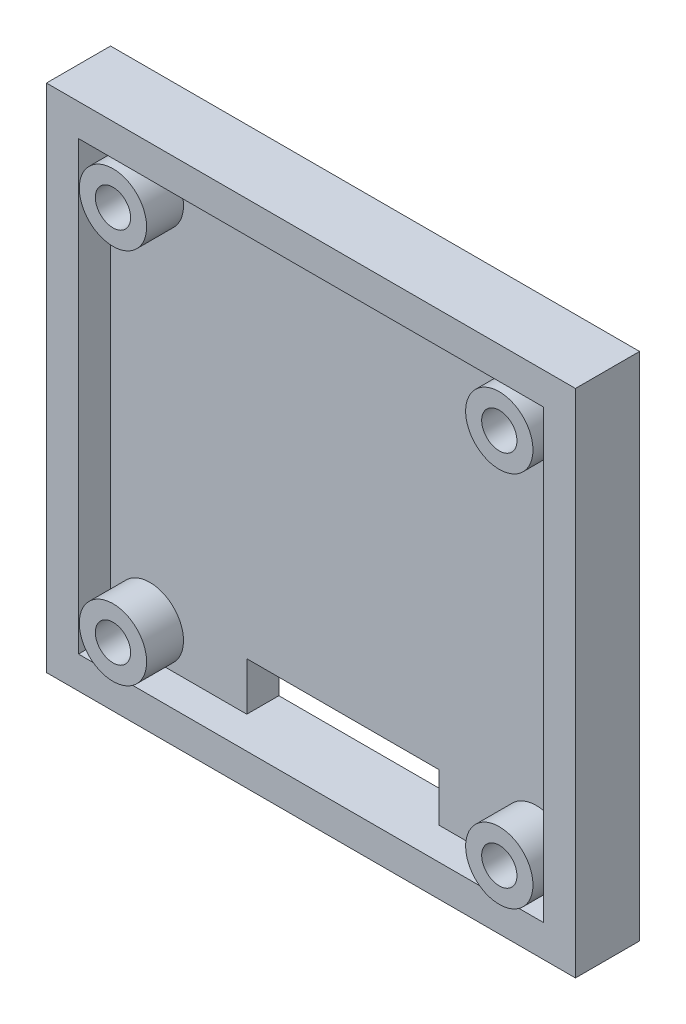
SolidWorks part; units mm, degrees
ref_plane "Front Plane" through (0, 0, 0) normal (0, 0, 1) x (1, 0, 0)
ref_plane "Top Plane" through (0, 0, 0) normal (0, 1, 0) x (1, 0, 0)
ref_plane "Right Plane" through (0, 0, 0) normal (1, 0, 0) x (0, 0, -1)
sketch "Sketch1" plane through (0, 0, 0) normal (0, 0, 1) x (1, 0, 0)
  line L1 (16.5, -15.925) -> (-16.5, -15.925)
  line L2 (16.5, -15.925) -> (16.5, 15.925)
  line L3 (16.5, 15.925) -> (-16.5, 15.925)
  line L4 (-16.5, -15.925) -> (-16.5, 15.925)
  line L5 (16.5, -15.925) -> (-16.5, 15.925) construction
  line L6 (16.5, 15.925) -> (-16.5, -15.925) construction
  line L7 (-12.05, -11.925) -> (12.05, -11.925)
  line L8 (-12.05, -11.925) -> (-12.05, 11.575)
  line L9 (-12.05, 11.575) -> (12.05, 11.575)
  line L10 (12.05, -11.925) -> (12.05, 11.575)
  line L11 (-12.05, -11.925) -> (12.05, 11.575) construction
  line L12 (-12.05, 11.575) -> (12.05, -11.925) construction
  line L17 (-6, -10.925) -> (6, -10.925)
  line L18 (-6, -10.925) -> (-6, -13.925)
  line L19 (-6, -13.925) -> (6, -13.925)
  line L20 (6, -10.925) -> (6, -13.925)
  circle A0 centre (-12.05, 11.575) radius 1.1
  circle A1 centre (12.05, 11.575) radius 1.1
  circle A2 centre (-12.05, -11.925) radius 1.1
  circle A3 centre (12.05, -11.925) radius 1.1
  point P0 (0, 0)
  point P6 (0, -0.175)
  dimension "D7" = 2.2
  dimension "D1" = 24.1
  dimension "D2" = 23.5
  dimension "D3" = 4
  dimension "D4" = 4.45
  dimension "D5" = 31.85
  dimension "D6" = 33
  dimension "D8" = 12
  dimension "D9" = 3
  dimension "D10" = 2
  dimension "D11" = 10.5
extrude "Boss-Extrude1" add sketch "Sketch1" along normal blind 2 contours L4 L1 L2 L3 A3 L7 A2 L8 A0 L9 A1 L10 | A3 L10 A1 L9 A0 L8 A2 L7 L18 L19 L20
sketch "Sketch2" plane through (0, 0, 2) normal (0, 0, 1) x (1, 0, 0)
  circle A0 centre (-12.05, 11.575) radius 2.1
  circle A1 centre (-12.05, -11.925) radius 2.1
  circle A2 centre (12.05, -11.925) radius 2.1
  circle A3 centre (12.05, 11.575) radius 2.1
  circle A4 centre (12.05, 11.575) radius 1.1
  circle A5 centre (-12.05, 11.575) radius 1.1
  circle A6 centre (-12.05, -11.925) radius 1.1
  circle A7 centre (12.05, -11.925) radius 1.1
  dimension "D1" = 1
extrude "Boss-Extrude2" add sketch "Sketch2" along normal blind 2.3
sketch "Sketch3" plane through (0, 0, 2) normal (0, 0, 1) x (1, 0, 0)
  line L1 (-16.5, 15.925) -> (16.5, 15.925)
  line L2 (-16.5, 15.925) -> (-16.5, -15.925)
  line L3 (-16.5, -15.925) -> (16.5, -15.925)
  line L4 (16.5, 15.925) -> (16.5, -15.925)
  line L5 (-14.5, 13.925) -> (14.5, 13.925)
  line L6 (-14.5, 13.925) -> (-14.5, -13.925)
  line L7 (-14.5, -13.925) -> (14.5, -13.925)
  line L8 (14.5, 13.925) -> (14.5, -13.925)
  dimension "D1" = 2
  dimension "D2" = 2
  dimension "D3" = 2
  dimension "D4" = 2
extrude "Boss-Extrude3" add sketch "Sketch3" along normal blind 2
